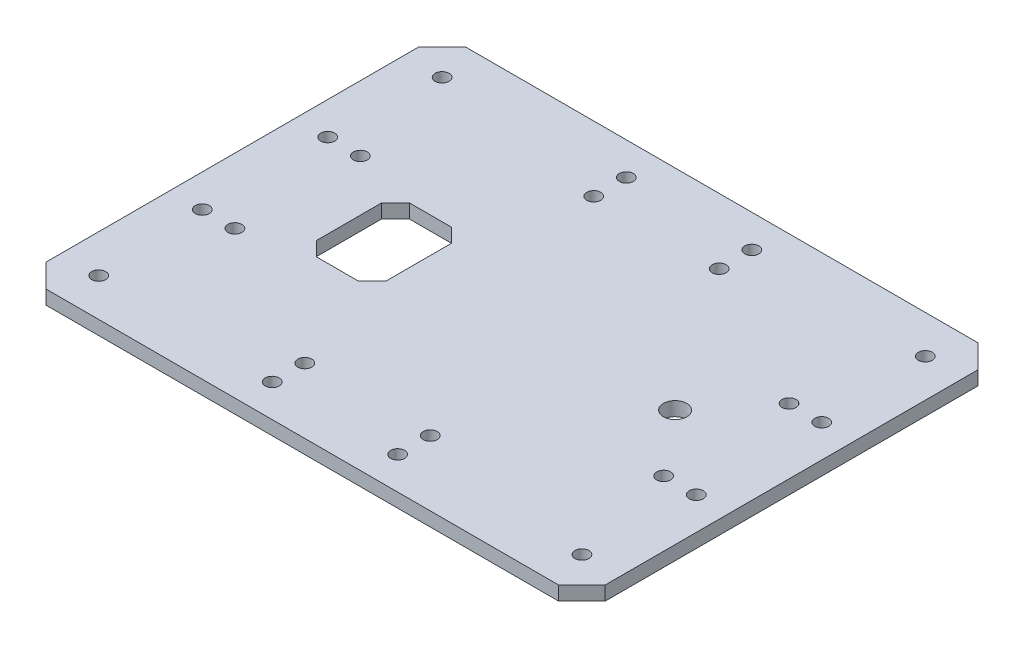
SolidWorks part; units mm, degrees
ref_plane "Front Plane" through (0, 0, 0) normal (0, 0, 1) x (1, 0, 0)
ref_plane "Top Plane" through (0, 0, 0) normal (0, 1, 0) x (1, 0, 0)
ref_plane "Right Plane" through (0, 0, 0) normal (1, 0, 0) x (0, 0, -1)
sketch "Sketch1" plane through (0, 0, 0) normal (0, 1, 0) x (1, 0, 0)
  line L1 (-60, 45) -> (60, 45)
  line L2 (-60, 45) -> (-60, -45)
  line L3 (-60, -45) -> (60, -45)
  line L4 (60, 45) -> (60, -45)
  line L5 (-60, 45) -> (60, -45) construction
  line L6 (-60, -45) -> (60, 45) construction
  point P0 (0, 0)
  dimension "D1" = 90
  dimension "D2" = 120
extrude "Boss-Extrude1" add sketch "Sketch1" along normal blind 3
chamfer "Chamfer1" distance 5 angle 45 4 edges at (-60, 1.5, 45) (-60, 1.5, -45) (60, 1.5, -45) (60, 1.5, 45)
sketch "Sketch5" plane through (0, 0, 0) normal (0, -1, 0) x (1, 0, 0)
  line L3 (-57.5, 42.5) -> (-6.9406, -8.0594) construction
  line L4 (-55, 45) -> (-60, 40) construction
  point P6 (-51.8431, 36.8431)
  dimension "D1" = 8
hole_wizard "Ø3.0 (3) Diameter Hole2" positions "Sketch5" profile "Sketch6" hole size "Ø3.0" standard "ANSI Metric" end condition through all
sketch "Sketch6" plane through (-51.8431, 0, 36.8431) normal (1, 0, 0) x (0, 0, -1)
  line L0 (0, 0) -> (0, 3)
  line L1 (0, 3) -> (1.5, 3)
  line L2 (1.5, 3) -> (1.5, 0)
  line L5 (1.5, 0) -> (0, 0)
  line L11 (0, -6.35) -> (0, 107.95) construction
  dimension "Thru Hole Dia." = 3
  dimension "Thru Hole Depth" = 3
mirror "Mirror1" about plane through (0, 0, 0) normal (0, 0, 1) of "Ø3.0 (3) Diameter Hole2" second plane through (0, 0, 0) second plane normal (1, 0, 0)
sketch "Sketch7" plane through (0, 3, 0) normal (0, 1, 0) x (1, 0, 0)
  point P0 (46, -13.463)
  point P1 (53, -13.463)
  point P3 (46, 13.463)
  point P5 (53, 13.463)
  point P7 (13.463, -31)
  point P9 (13.463, -38)
  point P11 (-13.463, -38)
  point P13 (-13.463, -31)
  point P15 (-46, -13.463)
  point P17 (-53, -13.463)
  point P19 (-46, 13.463)
  point P21 (-53, 13.463)
  point P23 (13.463, 31)
  point P25 (13.463, 38)
  point P27 (-13.463, 31)
  point P29 (-13.463, 38)
hole_wizard "Ø3.0 (3) Diameter Hole3" positions "Sketch7" profile "Sketch8" hole size "Ø3.0" standard "ANSI Metric" end condition through all
sketch "Sketch8" plane through (46, 3, 13.463) normal (1, 0, 0) x (0, 0, 1)
  line L0 (0, 0) -> (0, 3)
  line L1 (0, 3) -> (1.5, 3)
  line L2 (1.5, 3) -> (1.5, 0)
  line L5 (1.5, 0) -> (0, 0)
  line L11 (0, -6.35) -> (0, 107.95) construction
  dimension "Thru Hole Dia." = 3
  dimension "Thru Hole Depth" = 3
sketch "Sketch9" plane through (0, 0, 0) normal (0, -1, 0) x (-1, 0, 0)
  line L3 (-60, 0) -> (0, 0) construction
  line L4 (-60, -40) -> (-60, 40) construction
  point P17 (-35, 0)
  dimension "D1" = 25
hole_wizard "Ø5.0 (5) Diameter Hole1" positions "Sketch9" profile "Sketch10" hole size "Ø5.0" standard "ANSI Metric" end condition through all
sketch "Sketch10" plane through (35, 0, 0) normal (1, 0, 0) x (0, 0, -1)
  line L0 (0, 0) -> (0, 3)
  line L1 (0, 3) -> (2.5, 3)
  line L2 (2.5, 3) -> (2.5, 0)
  line L5 (2.5, 0) -> (0, 0)
  line L11 (0, -6.35) -> (0, 107.95) construction
  dimension "Thru Hole Dia." = 5
  dimension "Thru Hole Depth" = 3
sketch "Sketch11" plane through (0, 0, 0) normal (0, -1, 0) x (-1, 0, 0)
  line L0 (60, 40) -> (60, -40) construction
  line L1 (35, -10) -> (20, -10)
  line L2 (35, -10) -> (35, 10)
  line L3 (35, 10) -> (20, 10)
  line L4 (20, -10) -> (20, 10)
  line L5 (60, 0) -> (0, 0) construction
  point P9 (35, 0)
  dimension "D1" = 20
  dimension "D2" = 15
  dimension "D3" = 25
extrude "Cut-Extrude1" cut sketch "Sketch11" against normal through all
chamfer "Chamfer2" distance 3 angle 45 4 edges at (-35, 1.5, -10) (-20, 1.5, -10) (-20, 1.5, 10) (-35, 1.5, 10)
